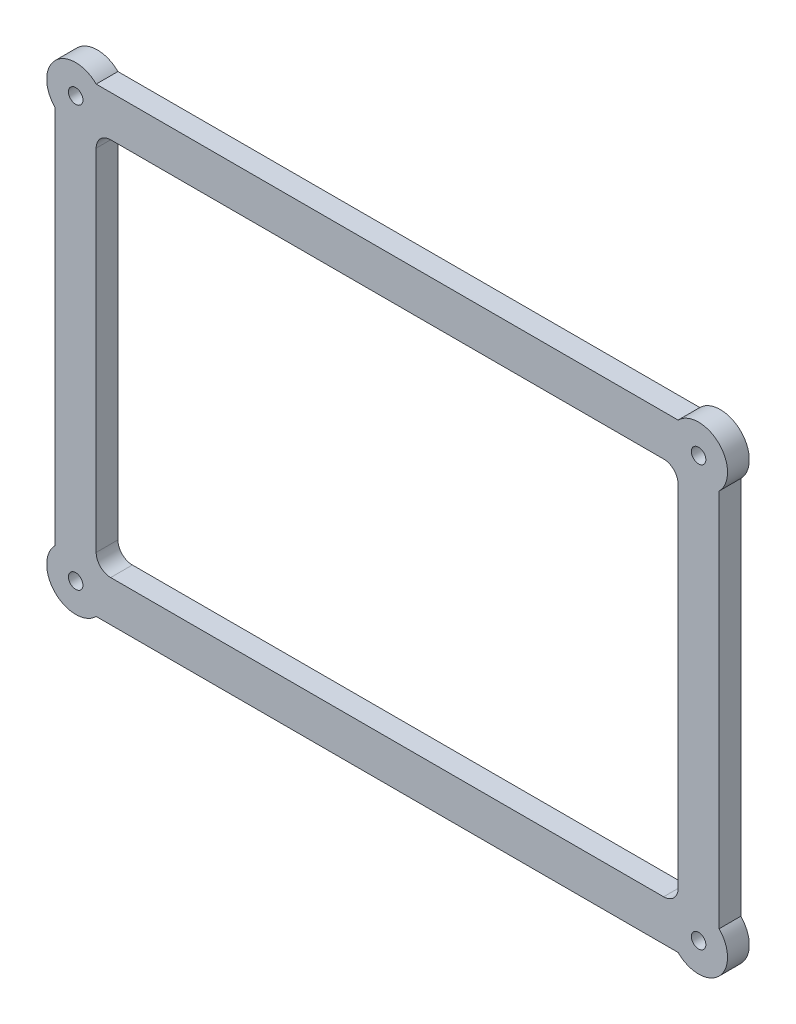
SolidWorks part; units mm, degrees
ref_plane "前视基准面" through (0, 0, 0) normal (0, 0, 1) x (1, 0, 0)
ref_plane "上视基准面" through (0, 0, 0) normal (0, 1, 0) x (1, 0, 0)
ref_plane "右视基准面" through (0, 0, 0) normal (1, 0, 0) x (0, 0, -1)
other "Configuration Table"
sketch "草图1" plane through (0, 0, 0) normal (0, 0, 1) x (1, 0, 0)
  line L1 (0, 0) -> (86, 0) construction
  line L2 (0, 0) -> (0, 58) construction
  line L3 (0, 58) -> (86, 58) construction
  line L4 (86, 0) -> (86, 58) construction
  line L5 (2.8284, 60.8284) -> (83.1716, 60.8284)
  line L7 (2.8284, 55.1716) -> (83.1716, 55.1716)
  line L10 (-2.8284, 55.1716) -> (-2.8284, 2.8284)
  line L12 (2.8284, 55.1716) -> (2.8284, 2.8284)
  line L13 (2.8284, 2.8284) -> (83.1716, 2.8284)
  line L15 (2.8284, -2.8284) -> (83.1716, -2.8284)
  line L18 (83.1716, 2.8284) -> (83.1716, 55.1716)
  line L20 (88.8284, 2.8284) -> (88.8284, 55.1716)
  circle A0 centre (0, 58) radius 1
  circle A1 centre (0, 0) radius 1
  circle A2 centre (86, 58) radius 1
  circle A3 centre (86, 0) radius 1
  arc A4 (2.8284, 60.8284) -> (-2.8284, 55.1716) centre (0, 58) ccw
  arc A6 (83.1716, -2.8284) -> (88.8284, 2.8284) centre (86, 0) ccw
  arc A7 (-2.8284, 2.8284) -> (2.8284, -2.8284) centre (0, 0) ccw
  arc A8 (88.8284, 55.1716) -> (83.1716, 60.8284) centre (86, 58) ccw
  circle A9 centre (0, 58) radius 4 construction
  circle A11 centre (86, 0) radius 4 construction
  circle A12 centre (0, 0) radius 4 construction
  point P10 (90, 58)
  point P12 (4, 0)
  point P26 (82.9528, 2.5913)
  point P29 (83.1244, 60.7804)
  point P31 (2.6922, 55.0416)
  point P32 (83.3078, 54.9264)
  point P33 (0, 0)
  point P34 (0, 0)
  point P35 (4, 58)
  point P37 (90, 0)
  dimension "D3" = 2
  dimension "D1" = 86
  dimension "D2" = 58
  dimension "D4" = 3
extrude "凸台-拉伸1" add sketch "草图1" along normal blind 3
fillet "圆角1" radius 2 4 edges at (2.8284, 2.8284, 1.5) (83.1716, 2.8284, 1.5) (83.1716, 55.1716, 1.5) (2.8284, 55.1716, 1.5)
